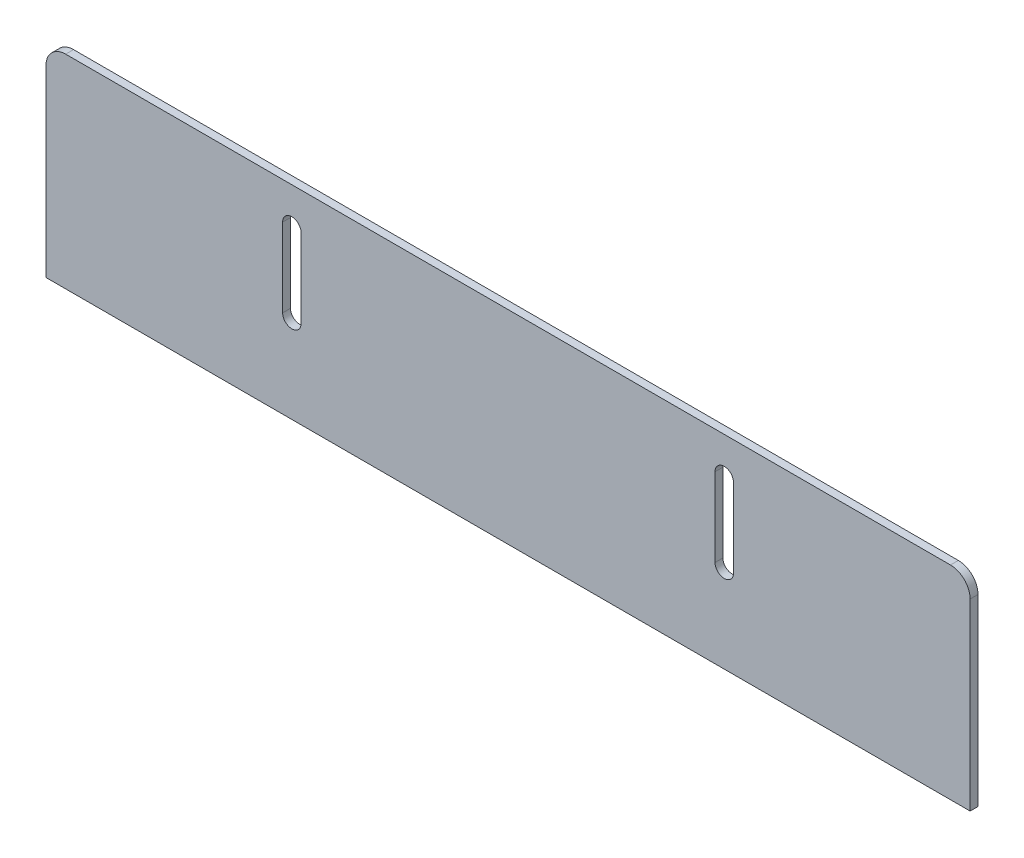
SolidWorks part; units mm, degrees
ref_plane "前视基准面" through (0, 0, 0) normal (0, 0, 1) x (1, 0, 0)
ref_plane "上视基准面" through (0, 0, 0) normal (0, 1, 0) x (1, 0, 0)
ref_plane "右视基准面" through (0, 0, 0) normal (1, 0, 0) x (0, 0, -1)
sketch "草图1" plane through (0, 0, 0) normal (0, 0, 1) x (1, 0, 0)
  line L0 (117.5507, 51.7223) -> (117.5507, 42.3183)
  line L1 (0, 0) -> (235.1014, 0)
  line L2 (0, 0) -> (0, 46.7223)
  line L3 (5, 51.7223) -> (230.1014, 51.7223)
  line L4 (235.1014, 0) -> (235.1014, 46.7223)
  line L5 (60.1997, 42.3183) -> (60.1997, 22.3183)
  line L6 (64.9017, 42.3183) -> (64.9017, 22.3183)
  line L7 (170.1997, 42.3183) -> (170.1997, 22.3183)
  line L8 (174.9017, 42.3183) -> (174.9017, 22.3183)
  arc A0 (64.9017, 42.3183) -> (60.1997, 42.3183) centre (62.5507, 42.3183) ccw
  arc A1 (60.1997, 22.3183) -> (64.9017, 22.3183) centre (62.5507, 22.3183) ccw
  arc A2 (174.9017, 22.3183) -> (170.1997, 22.3183) centre (172.5507, 22.3183) cw
  arc A3 (170.1997, 42.3183) -> (174.9017, 42.3183) centre (172.5507, 42.3183) cw
  arc A4 (235.1014, 46.7223) -> (230.1014, 51.7223) centre (230.1014, 46.7223) ccw
  arc A5 (0, 46.7223) -> (5, 51.7223) centre (5, 46.7223) cw
  dimension "D1" = 55
  dimension "D3" = 5
  dimension "D2" = 20
extrude "凸台-拉伸1" add sketch "草图1" along normal blind 2
